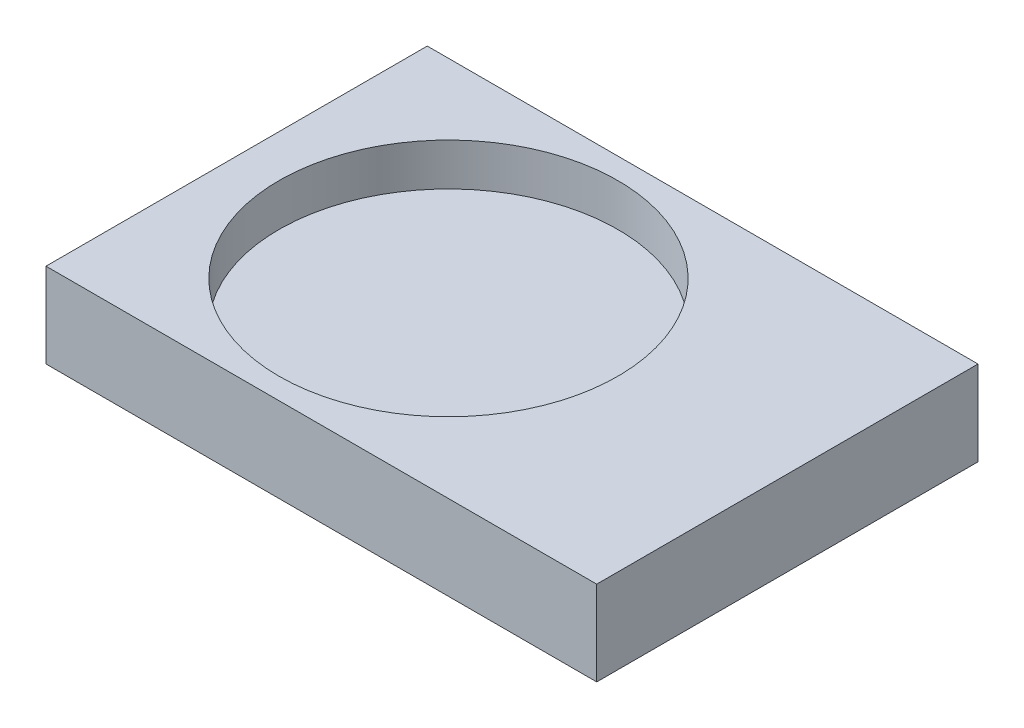
SolidWorks part; units mm, degrees
material "Oak"
ref_plane "Front Plane" through (0, 0, 0) normal (0, 0, 1) x (1, 0, 0)
ref_plane "Top Plane" through (0, 0, 0) normal (0, 1, 0) x (1, 0, 0)
ref_plane "Right Plane" through (0, 0, 0) normal (1, 0, 0) x (0, 0, -1)
sketch "Sketch1" plane through (0, 0, 0) normal (0, 1, 0) x (1, 0, 0)
  line L1 (0, 0) -> (650, 0)
  line L2 (0, 0) -> (0, 450)
  line L3 (0, 450) -> (650, 450)
  line L4 (650, 0) -> (650, 450)
  dimension "D1" = 650
  dimension "D2" = 450
extrude "Boss-Extrude1" add sketch "Sketch1" along normal blind 100
sketch "Sketch2" plane through (0, 100, 0) normal (0, 1, 0) x (1, 0, 0)
  line L0 (0, 450) -> (0, 0) construction
  line L1 (0, 0) -> (650, 0) construction
  circle A0 centre (250, 225) radius 200
  dimension "D1" = 250
  dimension "D2" = 225
extrude "Cut-Extrude1" cut sketch "Sketch2" against normal blind 50
